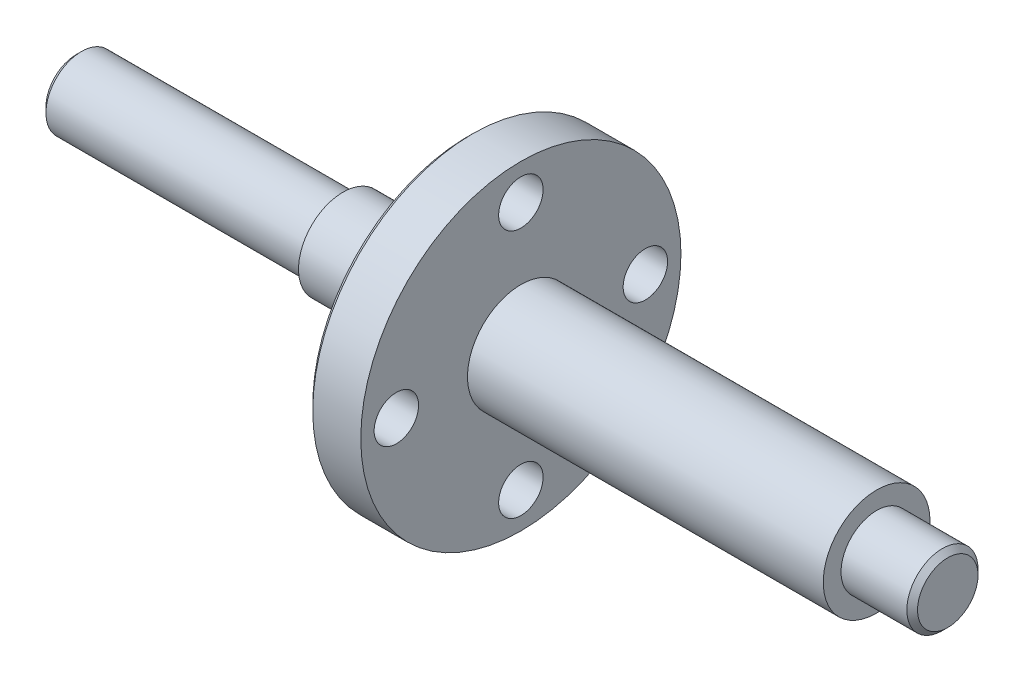
SolidWorks part; units mm, degrees
material "AISI 1045 钢，冷拔"
ref_plane "前视基准面" through (0, 0, 0) normal (0, 0, 1) x (1, 0, 0)
ref_plane "上视基准面" through (0, 0, 0) normal (0, 1, 0) x (1, 0, 0)
ref_plane "右视基准面" through (0, 0, 0) normal (1, 0, 0) x (0, 0, -1)
sketch "草图1" plane through (0, 0, 0) normal (1, 0, 0) x (0, 0, -1)
  circle A0 centre (0, 0) radius 2
  dimension "D1" = 4
extrude "凸台-拉伸1" add sketch "草图1" along normal blind 15
sketch "草图2" plane through (15, 0, 0) normal (1, 0, 0) x (0, 0, -1)
  circle A0 centre (0, 0) radius 2.5
  dimension "D1" = 5
extrude "凸台-拉伸2" add sketch "草图2" along normal blind 4
sketch "草图3" plane through (19, 0, 0) normal (1, 0, 0) x (0, 0, -1)
  circle A0 centre (0, 0) radius 3
  dimension "D1" = 6
extrude "凸台-拉伸3" add sketch "草图3" along normal blind 3
sketch "草图4" plane through (22, 0, 0) normal (1, 0, 0) x (0, 0, -1)
  circle A0 centre (0, 0) radius 9
  dimension "D1" = 18
extrude "凸台-拉伸4" add sketch "草图4" along normal blind 3
sketch "草图5" plane through (25, 0, 0) normal (1, 0, 0) x (0, 0, -1)
  circle A0 centre (0, 0) radius 3
  dimension "D1" = 6
extrude "凸台-拉伸5" add sketch "草图5" along normal blind 20
sketch "草图8" plane through (45, 0, 0) normal (1, 0, 0) x (0, 0, -1)
  circle A0 centre (0, 0) radius 2
  dimension "D1" = 4
extrude "凸台-拉伸6" add sketch "草图8" along normal blind 4
hole_wizard "M3 螺纹孔2" positions "草图10" profile "草图9" tap size "M3" standard "Gb" end condition up to next
sketch "草图10" plane through (22, 0, 0) normal (-1, 0, 0) x (0, 0, 1)
  point P0 (0, 7)
  dimension "D1" = 7
sketch "草图9" plane through (22, 7, 0) normal (0, 1, 0) x (0, 0, 1)
  line L0 (0, 0) -> (0, 3.001)
  line L1 (0, 3.001) -> (1.25, 3.001)
  line L2 (1.25, 3.001) -> (1.25, 0)
  line L5 (1.25, 0) -> (0, 0)
  line L11 (0, -6.35) -> (0, 107.95) construction
  dimension "通孔螺纹孔钻头直径" = 2.5
  dimension "通孔螺纹孔钻头深度" = 3.001
cosmetic thread "孔螺蚊线2" parameters "D2"=3
pattern_circular "阵列(圆周)2" count 4 over 360 about axis through (0, 0, 0) along (1, 0, 0) of "M3 螺纹孔2"
chamfer "倒角1" distance 0.3 angle 45 3 edges at (22, 0, -9) (0, 0, -2) (49, 0, -2)
sketch "草图11" plane through (49, 0, 0) normal (1, 0, 0) x (0, 0, -1)
  circle A0 centre (0, 0) radius 2.5
  circle A1 centre (0, 0) radius 2
  dimension "D1" = 4
